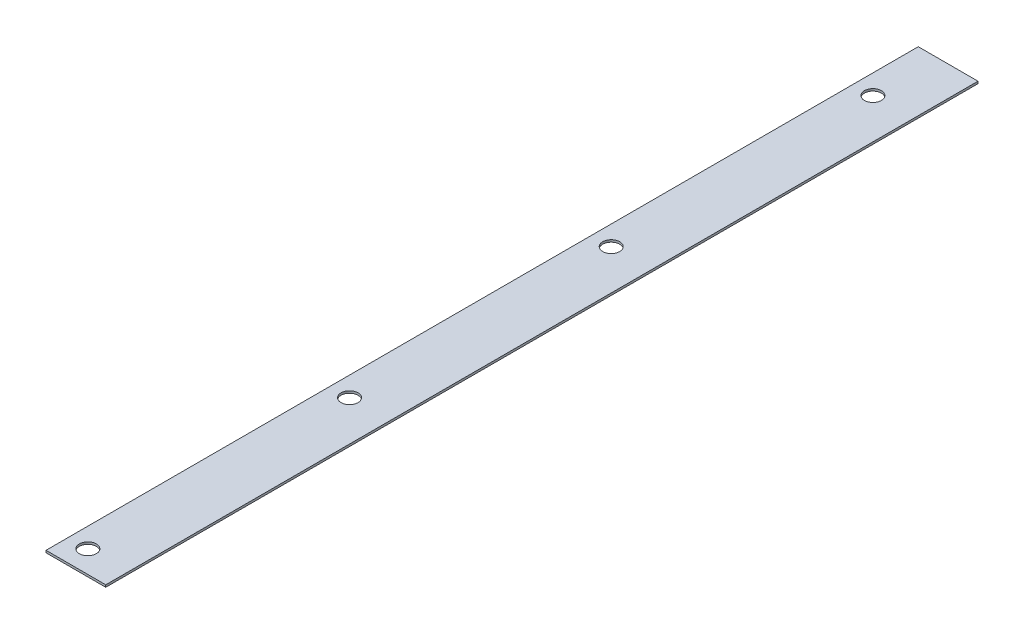
SolidWorks part; units mm, degrees
ref_plane "Plan de face" through (0, 0, 0) normal (0, 0, 1) x (1, 0, 0)
ref_plane "Plan de dessus" through (0, 0, 0) normal (0, 1, 0) x (1, 0, 0)
ref_plane "Plan de droite" through (0, 0, 0) normal (1, 0, 0) x (0, 0, -1)
sketch "Esquisse1" plane through (0, 0, 0) normal (0, 0, 1) x (1, 0, 0)
  line L0 (0, 0) -> (13.7, 0)
  line L1 (13.7, 0.5) -> (13.7, 0)
  line L2 (13.7, 0.5) -> (0, 0.5)
  line L3 (0, 0.5) -> (0, 0)
  dimension "D1" = 13.7
  dimension "D2" = 0.5
extrude "Boss.-Extru.1" add sketch "Esquisse1" along normal blind 200
sketch "Esquisse2" plane through (0, 0.5, 0) normal (0, 1, 0) x (1, 0, 0)
  circle A0 centre (4.5, -14.9) radius 1.95
  circle A1 centre (4.5, -74.9) radius 1.95
  circle A2 centre (4.5, -134.9) radius 1.95
  circle A3 centre (4.5, -194.9) radius 1.95
  dimension "D1" = 3.9
  dimension "D2" = 4.5
  dimension "D3" = 14.9
  dimension "D5" = 60
  dimension "D4" = 4
extrude "Enlèv. mat.-Extru.1" cut sketch "Esquisse2" against normal up to next
